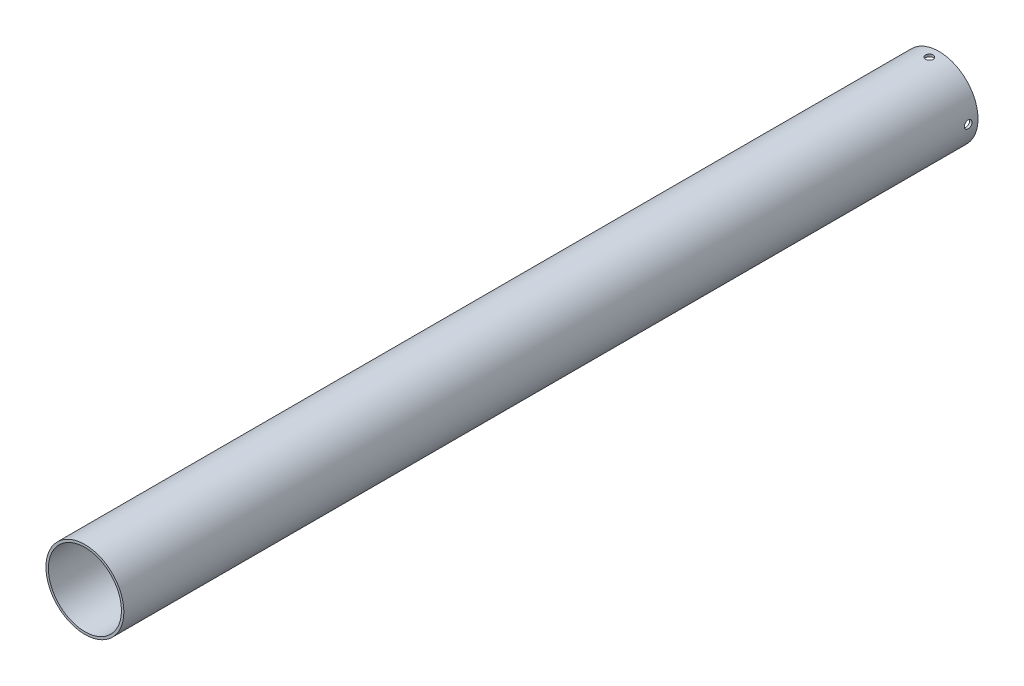
SolidWorks part; units mm, degrees
material "PC High Viscosity"
ref_plane "Front Plane" through (0, 0, 0) normal (0, 0, 1) x (1, 0, 0)
ref_plane "Top Plane" through (0, 0, 0) normal (0, 1, 0) x (1, 0, 0)
ref_plane "Right Plane" through (0, 0, 0) normal (1, 0, 0) x (0, 0, -1)
sketch "Sketch1" plane through (0, 0, 0) normal (0, 0, 1) x (1, 0, 0)
  circle A0 centre (0, 0) radius 23.8125
  circle A1 centre (0, 0) radius 25.4
  dimension "D1" = 50.8
  dimension "D2" = 47.625
extrude "Boss-Extrude1" add sketch "Sketch1" along normal mid plane 556.685
sketch "Sketch2" plane through (0, 0, 0) normal (1, 0, 0) x (0, 0, -1)
  line L0 (278.3425, -25.4) -> (278.3425, 25.4) construction
  circle A1 centre (271.9925, 0) radius 2.4892
  dimension "D1" = 4.9784
  dimension "D2" = 6.35
extrude "Cut-Extrude1" cut sketch "Sketch2" against normal through all both and the other way through all
sketch "Sketch3" plane through (0, 0, 0) normal (0, 1, 0) x (1, 0, 0)
  line L0 (25.4, 278.3425) -> (-25.4, 278.3425) construction
  circle A0 centre (0, 271.9925) radius 2.4892
  dimension "D1" = 4.9784
  dimension "D2" = 6.35
extrude "Cut-Extrude2" cut sketch "Sketch3" against normal through all both and the other way through all
equation "\"D1@Boss-Extrude1\"=21.125in+3.625mm"
